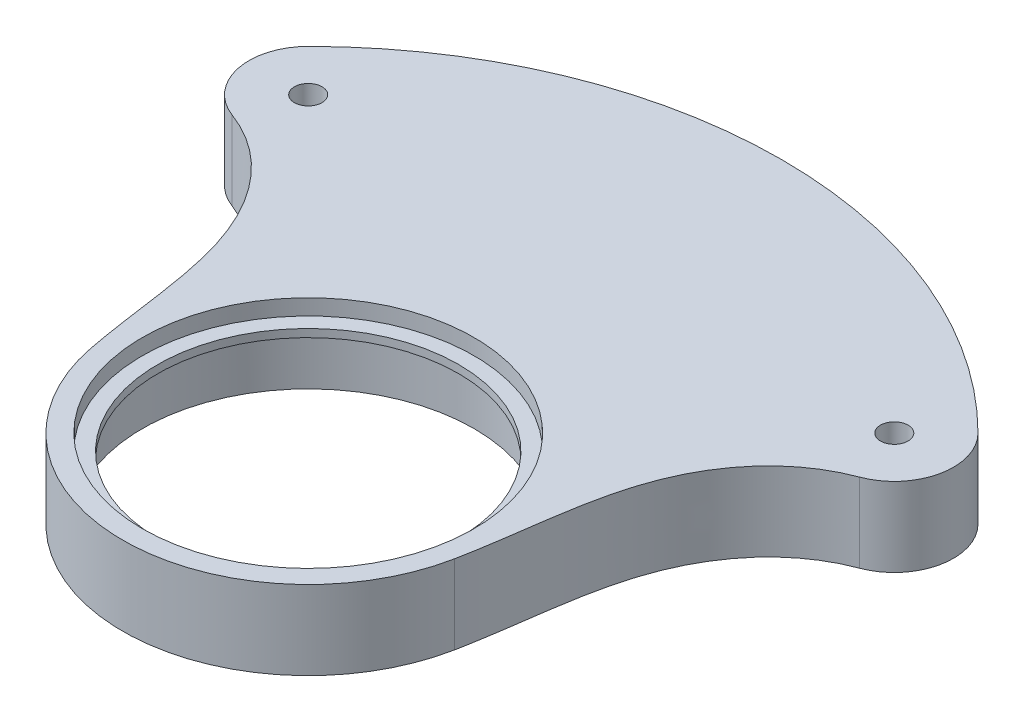
SolidWorks part; units mm, degrees
ref_plane "Front Plane" through (0, 0, 0) normal (0, 0, 1) x (1, 0, 0)
ref_plane "Top Plane" through (0, 0, 0) normal (0, 1, 0) x (1, 0, 0)
ref_plane "Right Plane" through (0, 0, 0) normal (1, 0, 0) x (0, 0, -1)
sketch "Sketch2" plane through (0, 0, 0) normal (0, 1, 0) x (1, 0, 0)
  line L0 (-31.8198, 31.8198) -> (-42.4264, 42.4264)
  line L1 (0, -55) -> (0, 55) construction
  line L2 (23.5, 0) -> (45, 0) construction
  circle A0 centre (0, 0) radius 45 construction
  circle A1 centre (0, 0) radius 60
  arc A2 (-42.4264, 42.4264) -> (-31.8198, 31.8198) centre (-37.1231, 37.1231) ccw
  arc A3 (42.4264, 42.4264) -> (31.8198, 31.8198) centre (37.1231, 37.1231) cw
  circle A4 centre (0, 0) radius 21
  circle A5 centre (0, 0) radius 23.5
  circle A6 centre (0, 0) radius 34.25 construction
  spline S0 degree 3 poles (-39.742, 30.0952) (-34.3086, 28.0705) (-24.8133, 17.3718) (-24.7508, 4.0744) (-23.0586, -4.5332) knots 0 0 0 0 0.392293 1 1 1 1
  spline S1 degree 3 poles (39.742, 30.0952) (34.3086, 28.0705) (24.8133, 17.3718) (24.7508, 4.0744) (23.0586, -4.5332) knots 0 0 0 0 0.392293 1 1 1 1
  point P23 (34.25, 0)
  dimension "D2" = 120
  dimension "D4" = 42
  dimension "D1" = 15
  dimension "D3" = 45
  dimension "D5" = 2.5
extrude "Boss-Extrude1" add sketch "Sketch2" along normal blind 10
sketch "Sketch3" plane through (0, 10, 0) normal (0, 1, 0) x (1, 0, 0)
  line L0 (0, 0) -> (-37.1231, 37.1231) construction
  line L1 (-37.1231, 37.1231) -> (37.1231, 37.1231) construction
  line L2 (37.1231, 37.1231) -> (0, 0) construction
  line L3 (0, -55) -> (0, 55) construction
  circle A0 centre (-37.1231, 37.1231) radius 1.75
  circle A1 centre (37.1231, 37.1231) radius 1.75
  dimension "D1" = 3.5
extrude "Cut-Extrude1" cut sketch "Sketch3" against normal up to next
sketch "Sketch5" plane through (0, 0, 0) normal (0, 0, 1) x (1, 0, 0)
  line L0 (-23.0586, 10) -> (-23.0586, 0) construction
  line L1 (-23.0586, 7) -> (-19.0586, 7)
  line L2 (-23.0586, 7) -> (-23.0586, 8)
  line L3 (-23.0586, 8) -> (-19.0586, 8)
  line L4 (-19.0586, 7) -> (-19.0586, 8)
  line L5 (-37.1231, 10) -> (37.1231, 10) construction
  line L6 (0, 10) -> (0, 0.557) construction
  dimension "D1" = 4
  dimension "D2" = 3
  dimension "D3" = 1
revolve "Revolve1" add sketch "Sketch5" angle 360 about L6
equation "\"Width\"= 10mm"
equation "\"Thick\"= 10mm"
equation "\"Diameter\"=120"
equation "\"D2@Sketch2\"= \"Diameter\""
equation "\"DegreeOfArc\"= 90deg"
equation "\"D3@Sketch2\"= \"DegreeOfArc\" / 2"
equation "\"D1@Boss-Extrude1\"= \"Thick\""
equation "\"D1@Sketch2\"=\"Width\"*1.5"
equation "\"D4@Sketch2\"=42"
